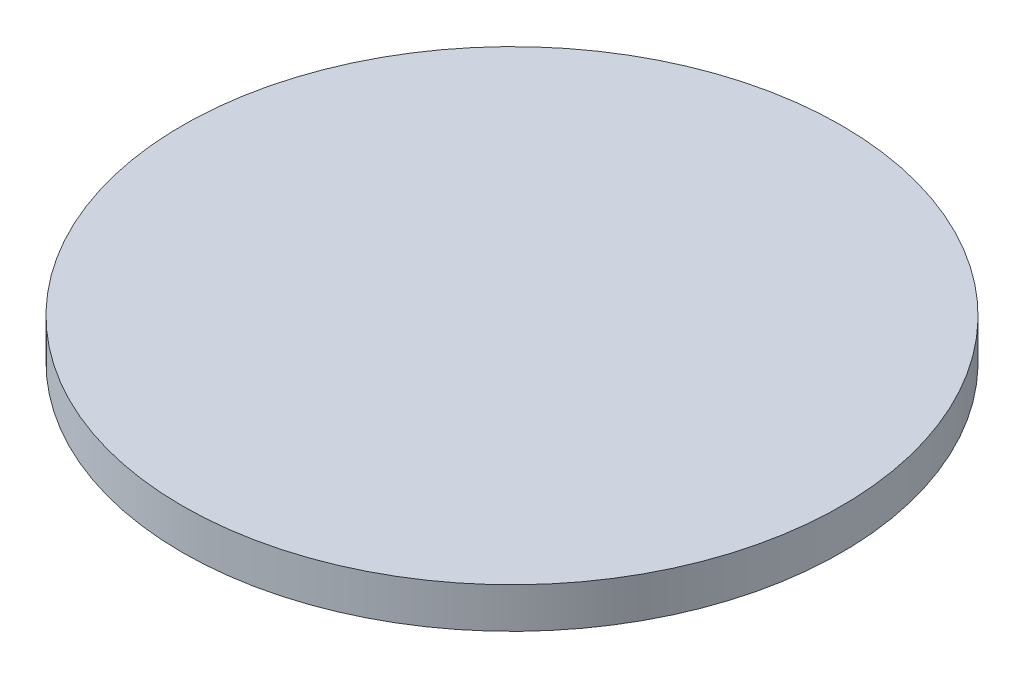
SolidWorks part; units mm, degrees
ref_plane "Front Plane" through (0, 0, 0) normal (0, 0, 1) x (1, 0, 0)
ref_plane "Top Plane" through (0, 0, 0) normal (0, 1, 0) x (1, 0, 0)
ref_plane "Right Plane" through (0, 0, 0) normal (1, 0, 0) x (0, 0, -1)
sketch "Sketch1" plane through (0, 0, 0) normal (0, 1, 0) x (1, 0, 0)
  circle A0 centre (0, 0) radius 24.4899
extrude "Boss-Extrude1" add sketch "Sketch1" along normal blind 3
